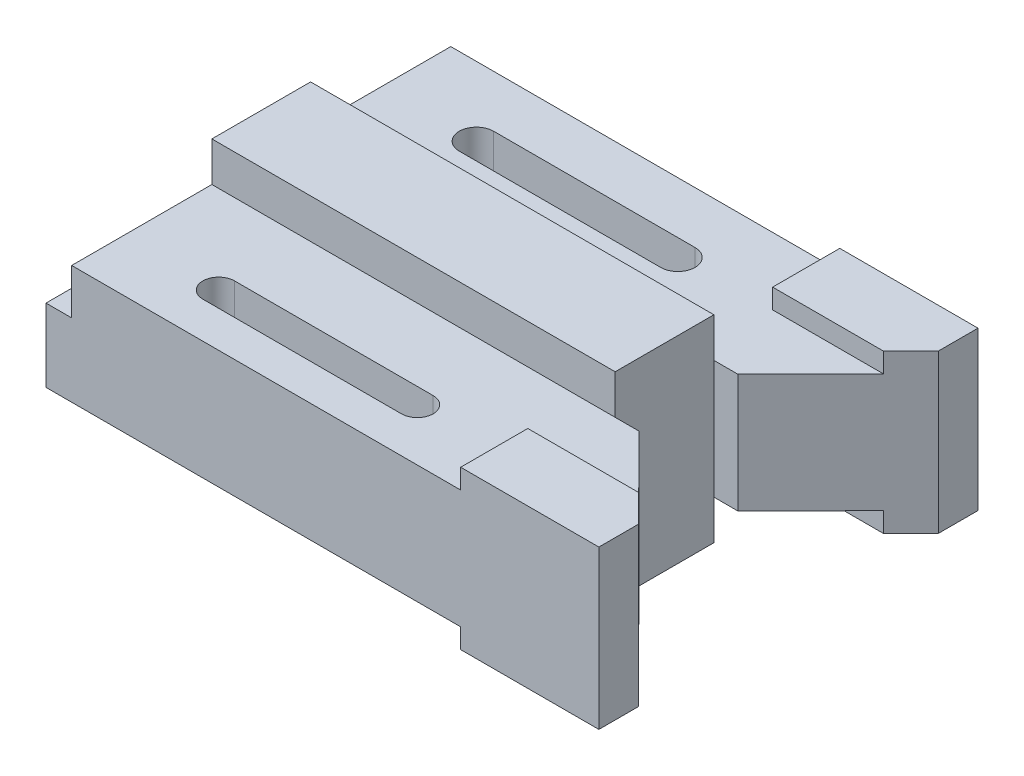
SolidWorks part; units mm, degrees
material "1060 Alloy"
ref_plane "Front Plane" through (0, 0, 0) normal (0, 0, 1) x (1, 0, 0)
ref_plane "Top Plane" through (0, 0, 0) normal (0, 1, 0) x (1, 0, 0)
ref_plane "Right Plane" through (0, 0, 0) normal (1, 0, 0) x (0, 0, -1)
sketch "Sketch1" plane through (0, 0, 0) normal (0, 1, 0) x (1, 0, 0)
  line L0 (0, 0) -> (108.6235, 0) construction
  line L1 (0, -48) -> (0, 48)
  line L2 (0, 48) -> (140, 48)
  line L3 (140, 48) -> (140, 38)
  line L4 (140, 38) -> (114.6859, 12.5)
  line L5 (114.6859, 12.5) -> (0, 12.5)
  line L6 (108.6235, 12.5) -> (108.6235, -12.5)
  line L17 (140, -48) -> (140, -38)
  line L18 (105, -48) -> (105, -31)
  line L19 (105, -31) -> (133, -31)
  line L20 (140, -38) -> (114.6859, -12.5)
  line L21 (114.6859, -12.5) -> (0, -12.5)
  line L23 (0, -48) -> (140, -48)
extrude "Boss-Extrude3" add sketch "Sketch1" along normal blind 30
sketch "Sketch3" plane through (0, 30, 0) normal (0, 1, 0) x (1, 0, 0)
  line L0 (108.6235, 12.5) -> (0, 12.5)
  line L1 (0, -48) -> (0, 48) construction
  line L2 (108.6235, -12.5) -> (0, -12.5)
  line L3 (0, 12.5) -> (0, -12.5)
  line L4 (108.6235, 12.5) -> (108.6235, -12.5)
extrude "Boss-Extrude4" add sketch "Sketch3" along normal blind 10
sketch "Sketch4" plane through (0, 30, 0) normal (0, 1, 0) x (1, 0, 0)
  line L0 (140, 48) -> (105, 48)
  line L1 (0, 48) -> (140, 48) construction
  line L2 (105, 48) -> (105, 31)
  line L3 (105, 31) -> (133.051, 31)
  line L4 (140, 38) -> (114.6859, 12.5) construction
  line L5 (0, 30.5) -> (-2.1721, 30.5)
  line L6 (0, 12.5) -> (0, 48) construction
  line L7 (30.5, 30.5) -> (81.5, 30.5) construction
  line L8 (30.5, 34.8607) -> (81.5, 34.8607)
  line L9 (30.5, 26.1393) -> (81.5, 26.1393)
  arc A0 (30.5, 34.8607) -> (30.5, 26.1393) centre (30.5, 30.5) ccw
  arc A1 (81.5, 26.1393) -> (81.5, 34.8607) centre (81.5, 30.5) ccw
  point P16 (56, 30.5)
  point P21 (0, 0)
  point P22 (0, 0)
  point P23 (0, 48)
  point P25 (0, 0)
  dimension "D1" = 17
  dimension "D2" = 17.5
  dimension "D3" = 51
  dimension "D4" = 140
  dimension "D5" = 30.5
  dimension "D6" = 35
  dimension "D7" = 10
extrude "Cut-Extrude2" cut sketch "Sketch4" against normal through all both and the other way through all contours L9 A1 L8 A0
sketch "Sketch5" plane through (0, 0, 0) normal (0, -1, 0) x (1, 0, 0)
  line L0 (108.6235, 12.5) -> (0, 12.5)
  line L1 (0, 48) -> (0, -48) construction
  line L2 (0, 12.5) -> (0, -12.5)
  line L3 (0, -12.5) -> (108.6235, -12.5)
  line L4 (108.6235, -12.5) -> (108.6235, 12.5) construction
  line L5 (108.6235, -12.5) -> (108.6235, 12.5)
extrude "Boss-Extrude5" add sketch "Sketch5" along normal blind 10
sketch "Sketch6" plane through (0, 0, 0) normal (0, -1, 0) x (1, 0, 0)
  line L7 (30.5, 34.7753) -> (80.795, 34.7753) construction
  line L8 (30.5, 38.7848) -> (80.795, 38.7848)
  line L9 (30.5, 30.7657) -> (80.795, 30.7657)
  arc A0 (30.5, 38.7848) -> (30.5, 30.7657) centre (30.5, 34.7753) ccw
  arc A1 (80.795, 30.7657) -> (80.795, 38.7848) centre (80.795, 34.7753) ccw
  point P15 (55.6475, 34.7753)
extrude "Cut-Extrude3" cut sketch "Sketch6" against normal through all both and the other way through all
sketch "Sketch10" plane through (0, 30, 0) normal (0, 1, 0) x (1, 0, 0)
  line L0 (140, 48) -> (105, 48)
  line L1 (0, 48) -> (140, 48) construction
  line L2 (105, 48) -> (105, 31)
  line L3 (105, 31) -> (133.051, 31)
  line L4 (140, 38) -> (114.6859, 12.5) construction
  line L5 (133.051, 31) -> (140, 38)
  line L6 (140, 38) -> (140, 48)
extrude "Boss-Extrude6" add sketch "Sketch10" along normal blind 5
sketch "Sketch12" plane through (0, 0, 0) normal (0, -1, 0) x (1, 0, 0)
  line L0 (140, 48) -> (105, 48)
  line L1 (0, 48) -> (140, 48) construction
  line L2 (105, 48) -> (105, 31)
  line L3 (105, 31) -> (133.051, 31)
  line L4 (140, 38) -> (114.6859, 12.5) construction
  line L5 (133.051, 31) -> (140, 38)
  line L6 (140, 38) -> (140, 48)
  line L7 (105, -48) -> (105, -31)
  line L8 (0, -48) -> (140, -48) construction
  line L9 (105, -48) -> (140, -48)
  line L10 (140, -48) -> (140, -38)
  line L11 (105, -31) -> (133.051, -31)
  line L12 (140, -38) -> (114.6859, -12.5) construction
  line L13 (133.051, -31) -> (140, -38)
extrude "Boss-Extrude7" add sketch "Sketch12" along normal blind 5
sketch "Sketch13" plane through (0, 30, 0) normal (0, 1, 0) x (1, 0, 0)
  line L0 (105, -48) -> (105, -31)
  line L1 (105, -48) -> (140, -48)
  line L2 (140, -48) -> (140, -38)
  line L3 (105, -31) -> (133.051, -31)
  line L4 (140, -38) -> (114.6859, -12.5) construction
  line L5 (133.051, -31) -> (140, -38)
extrude "Boss-Extrude8" add sketch "Sketch13" along normal blind 5
sketch "Sketch21" plane through (0, 0, -48) normal (0, 0, -1) x (-1, 0, 0)
sketch "Sketch22" plane through (0, 0, -48) normal (0, 0, -1) x (-1, 0, 0)
  line L0 (0, 30) -> (-6.5, 30)
  line L1 (0, 30) -> (-105, 30) construction
  line L2 (0, 30) -> (0, 18.5)
  line L3 (0, 30) -> (0, 0) construction
  line L4 (-6.5, 30) -> (-6.5, 18.5)
  line L5 (-6.5, 18.5) -> (0, 18.5)
extrude "Cut-Extrude4" cut sketch "Sketch22" against normal up to next
sketch "Sketch23" plane through (0, 0, -12.5) normal (0, 0, -1) x (-1, 0, 0)
  line L0 (-6.5, 30) -> (-6.5, 40)
  line L1 (-108.6235, 40) -> (0, 40) construction
  line L2 (-6.5, 40) -> (0, 40)
  line L3 (0, 40) -> (0, 30)
  line L4 (0, 30) -> (-6.5, 30)
extrude "Cut-Extrude5" cut sketch "Sketch23" against normal through all
sketch "Sketch24" plane through (0, 0, -12.5) normal (0, 0, -1) x (-1, 0, 0)
  line L0 (0, -10) -> (0, -5)
  line L1 (0, -10) -> (0, 0) construction
